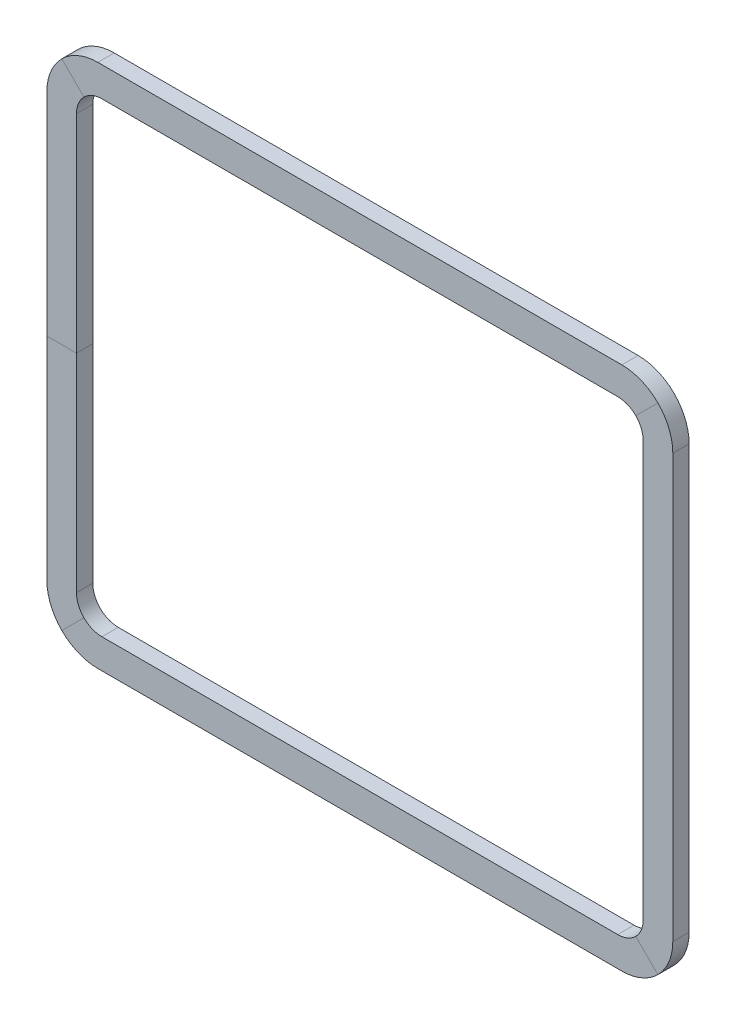
SolidWorks part; units mm, degrees
ref_plane "Front Plane" through (0, 0, 0) normal (0, 0, 1) x (1, 0, 0)
ref_plane "Top Plane" through (0, 0, 0) normal (0, 1, 0) x (1, 0, 0)
ref_plane "Right Plane" through (0, 0, 0) normal (1, 0, 0) x (0, 0, -1)
sketch "Sketch1" plane through (0, 0, 0) normal (0, 0, 1) x (1, 0, 0)
  line L1 (-30.7, 25.75) -> (30.7, 25.75)
  line L2 (-30.7, 25.75) -> (-30.7, -25.75)
  line L3 (-30.7, -25.75) -> (30.7, -25.75)
  line L4 (30.7, 25.75) -> (30.7, -25.75)
  line L5 (-30.7, 25.75) -> (30.7, -25.75) construction
  line L6 (-30.7, -25.75) -> (30.7, 25.75) construction
  point P0 (0, 0)
  dimension "D1" = 61.4
  dimension "D2" = 51.5
sketch "Sketch2" plane through (0, 0, 0) normal (0, 1, 0) x (1, 0, 0)
  line L0 (-30.7, 0) -> (30.7, 0) construction
  line L1 (-27.8, -1.6) -> (-30.7, -1.6)
  line L2 (-27.8, -1.6) -> (-27.8, 0)
  line L3 (-27.8, 0) -> (-30.7, 0)
  line L4 (-30.7, -1.6) -> (-30.7, 0)
  point P6 (0, 0)
  point P7 (0, 0)
  dimension "D1" = 1.6
  dimension "D2" = 2.9
sweep "Sweep1" add profiles "Sketch2" path "Sketch1"
fillet "Fillet1" radius 5 4 edges at (-30.7, 25.75, 0.8) (30.7, 25.75, 0.8) (30.7, -25.75, 0.8) (-30.7, -25.75, 0.8)
fillet "Fillet2" radius 2.5 4 edges at (27.8, 22.85, 0.8) (27.8, -22.85, 0.8) (-27.8, -22.85, 0.8) (-27.8, 22.85, 0.8)
